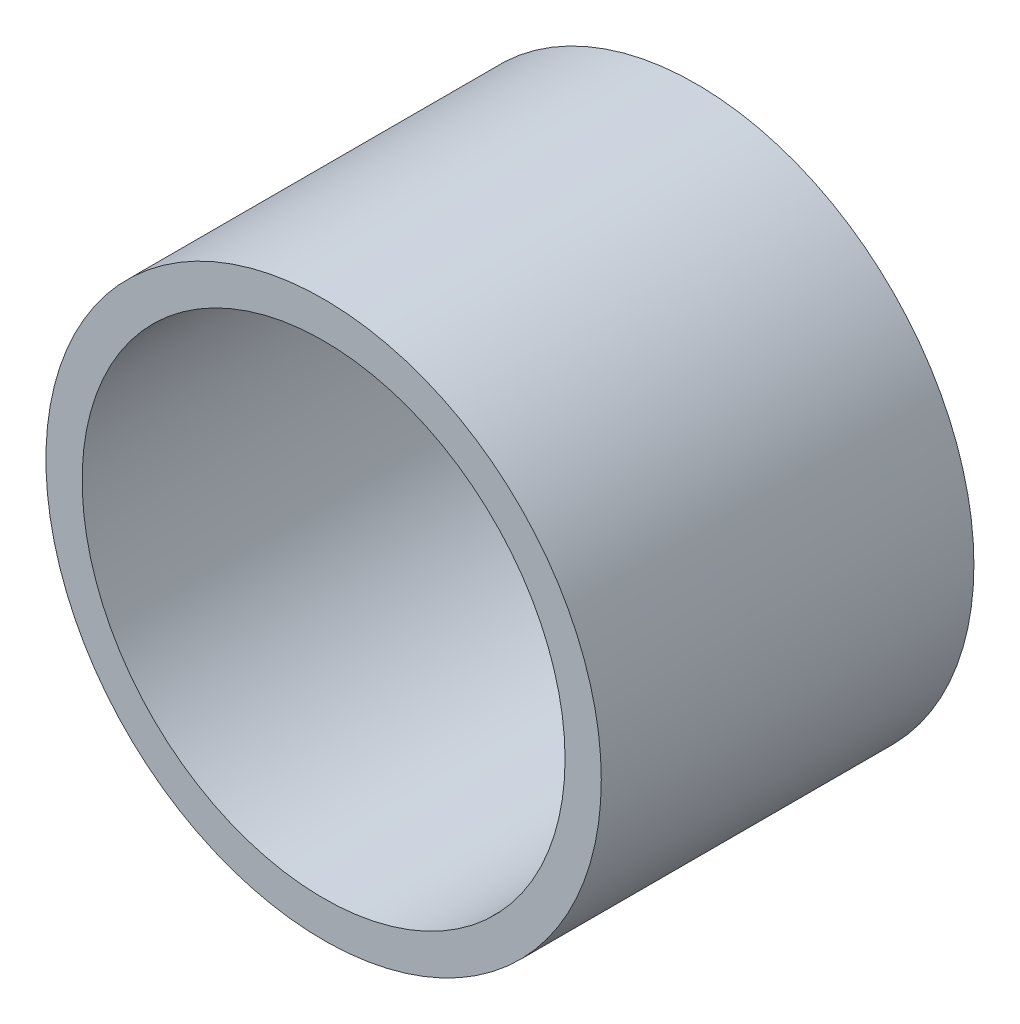
SolidWorks part; units mm, degrees
ref_plane "Front Plane" through (0, 0, 0) normal (0, 0, 1) x (1, 0, 0)
ref_plane "Top Plane" through (0, 0, 0) normal (0, 1, 0) x (1, 0, 0)
ref_plane "Right Plane" through (0, 0, 0) normal (1, 0, 0) x (0, 0, -1)
sketch "Sketch1" plane through (0, 0, 0) normal (0, 0, 1) x (1, 0, 0)
  circle A0 centre (0, 0) radius 44
  circle A1 centre (0, 0) radius 50.6
  dimension "D1" = 88
  dimension "D2" = 101.2
extrude "Boss-Extrude1" add sketch "Sketch1" along normal blind 67.9
